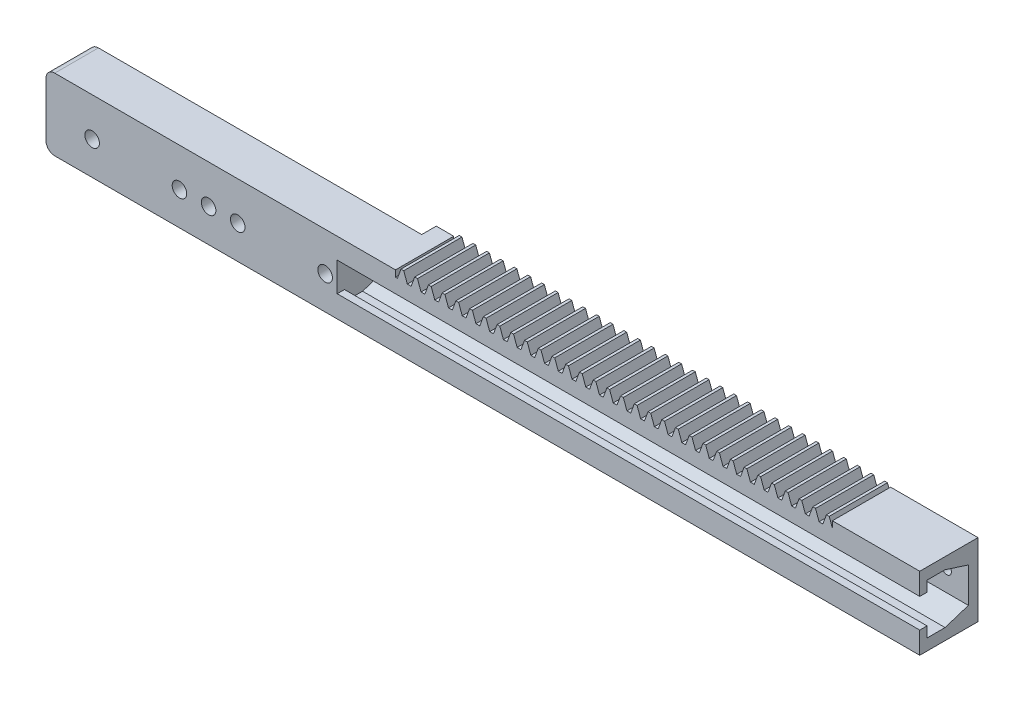
SolidWorks part; units mm, degrees
extrude "Blank" add sketch "BlankSke" against normal blind 20
sketch "BlankSke" plane through (0, 0, 0) normal (0, 0, 1) x (1, 0, 0)
  line L1 (0, 0) -> (150, 0)
  line L2 (0, 0) -> (0, 11.5)
  line L3 (0, 11.5) -> (150, 11.5)
  line L4 (150, 0) -> (150, 11.5)
  dimension "Length" = 150
  dimension "Blank_height" = 11.5
ref_plane "Plane1" through (0, 0, 0) normal (0, 0, 1) x (1, 0, 0)
ref_plane "Plane2" through (0, 0, 0) normal (0, 1, 0) x (1, 0, 0)
ref_plane "Plane3" through (0, 0, 0) normal (1, 0, 0) x (0, 0, -1)
other "Configuration Table"
sketch "HoldingSke" plane through (0, 0, 0) normal (0, 1, 0) x (1, 0, 0)
  line L0 (0, 0) -> (0.0928, 0.6602)
  line L1 (-15, 0) -> (100, 0) construction
  line L2 (0, 0) -> (-2.1039, 2.3779)
  line L3 (0, 0) -> (-11.863, 4.5341)
  line L4 (0, 0) -> (7.2428, 4.7035)
  line L5 (0, 0) -> (-23.7986, -8.8762)
  line L6 (0, 0) -> (-10.5278, -7.1032)
  line L9 (-71.009, 38.7566) -> (69.9449, 90.0596)
  line L10 (-76.2, 3.8779) -> (-66.2, 3.8779)
  line L11 (0, 0) -> (-20, 0)
  line L12 (-76.2, 101.6) -> (-76.147, 101.6)
  line L13 (24.9733, 27.94) -> (52.9518, 28.4284)
  line L14 (24.9733, 27.94) -> (24.9743, 27.94)
  line L15 (24.9733, 27.94) -> (100.4006, 29.5858)
  circle A0 centre (0, 0) radius 19.05
  circle A1 centre (0, 0) radius 5
  circle A2 centre (0, 0) radius 12.7
  dimension "MPH" = 10
  dimension "Diameter" = 38.1
  dimension "Num_teeth" = 33
  dimension "Pitch" = 0.6667
  dimension "Show_teeth" = 998
  dimension "Thickness" = 12.7
  dimension "Ap" = 20
  dimension "Pitch_height" = 10
  dimension "Width" = 20
  dimension "Backlash" = 0.053
  dimension "Addendum_fac" = 1
  dimension "Dedendum_fac" = 1.25
  dimension "Clearance_fac" = 0.25
  dimension "Dedendum_add" = 0.001
  dimension "Length" = 150
  dimension "Module" = 1.5
sketch "TooCutSkeIll" plane through (0, 0, 0) normal (0, 0, 1) x (1, 0, 0)
  line L0 (-1.8687, 11.4605) -> (-0.7447, 8.3724)
  line L1 (-0.3914, 8.125) -> (0.3914, 8.125)
  line L2 (0.7447, 8.3724) -> (1.8687, 11.4605)
  line L3 (150, 11.5) -> (0, 11.5) construction
  line L4 (0, 0) -> (0, 64.897) construction
  line L5 (-13.208, 10) -> (12.954, 10) construction
  line L6 (0, 0) -> (150, 0) construction
  line L7 (1.3371, 10) -> (1.3371, 48.7463) construction
  line L8 (-1.3371, 10) -> (-1.3371, 48.7463) construction
  line L9 (1.9251, 11.5) -> (1.9251, 11.5254)
  line L10 (-1.9251, 11.5) -> (-1.9251, 11.5254)
  line L11 (-1.9251, 11.5254) -> (1.9251, 11.5254)
  arc A0 (0.3914, 8.125) -> (0.7447, 8.3724) centre (0.3914, 8.501) ccw
  arc A1 (-0.7447, 8.3724) -> (-0.3914, 8.125) centre (-0.3914, 8.501) ccw
  arc A2 (1.9251, 11.5) -> (1.8687, 11.4605) centre (1.9251, 11.44) ccw
  arc A3 (-1.8687, 11.4605) -> (-1.9251, 11.5) centre (-1.9251, 11.44) ccw
  dimension "Pitch_height" = 10
  dimension "Addendum_plus" = 1.5254
  dimension "Pressure_angle" = 20
  dimension "Gap_width" = 2.6742
  dimension "Dedendum" = 1.875
extrude "ToothCutIll" [suppressed] cut sketch "TooCutSkeIll" against normal through all
sketch "TooCutSkeSim" plane through (0, 0, 0) normal (0, 0, 1) x (1, 0, 0)
  line L0 (0.6547, 8.125) -> (-0.6547, 8.125)
  line L1 (1.8923, 11.5254) -> (0.6547, 8.125)
  line L2 (0, 17.4625) -> (0, 53.467) construction
  line L3 (1.8923, 11.5254) -> (-1.8923, 11.5254)
  line L6 (-1.8923, 11.5254) -> (-0.6547, 8.125)
  line L9 (-1.3371, 10) -> (1.3371, 10) construction
  line L10 (0, 0) -> (150, 0) construction
  line L11 (1.3371, 10) -> (1.3371, 53.467) construction
  line L12 (-1.3371, 10) -> (-1.3371, 53.467) construction
  dimension "Pitch_height" = 10
  dimension "Addendum_plus" = 1.5254
  dimension "Pressure_angle" = 20
  dimension "Gap_width" = 2.6742
  dimension "Dedendum" = 1.875
extrude "ToothCutSim" cut sketch "TooCutSkeSim" against normal through all
pattern_linear "TeethCuts" count 32 spacing 4.7124 along (1, 0, 0) of "ToothCutIll", "ToothCutSim"
sketch "Sketch1" plane through (150, 0, 0) normal (1, 0, 0) x (0, 0, -1)
  line L0 (0, 8.5146) -> (0, 10.7146)
  line L1 (0, 8.5146) -> (0, 11.5) construction
  line L2 (0, 10.7146) -> (20, 10.7146)
  line L3 (20, 11.5) -> (20, 8.5146) construction
  line L7 (0, 8.5146) -> (0, 0)
  line L8 (0, 0) -> (20, 0)
  line L9 (20, 0) -> (20, 10.7146)
extrude "Boss-Extrude1" add sketch "Sketch1" along normal blind 20
sketch "Sketch2" plane through (0, 0, 0) normal (-1, 0, 0) x (0, 0, 1)
  line L0 (-20, 8.125) -> (-20, 10.325)
  line L1 (-20, 8.125) -> (-20, 11.5) construction
  line L2 (-20, 10.325) -> (0, 10.325)
  line L3 (0, 8.125) -> (0, 11.5) construction
  line L4 (0, 10.325) -> (0, 0)
  line L5 (0, 0) -> (-20, 0)
  line L6 (-20, 0) -> (-20, 8.125)
extrude "Boss-Extrude2" add sketch "Sketch2" along normal blind 20
sketch "Sketch3" plane through (0, 0, 0) normal (0, -1, 0) x (1, 0, 0)
  line L1 (-20, 0) -> (170, 0)
  line L2 (-20, 0) -> (-20, -20)
  line L3 (-20, -20) -> (170, -20)
  line L4 (170, 0) -> (170, -20)
extrude "Boss-Extrude3" add sketch "Sketch3" along normal blind 14.285
sketch "Sketch4" plane through (170, 0, 0) normal (1, 0, 0) x (0, 0, -1)
  line L2 (0, 10.7146) -> (0, -14.285) construction
  line L4 (2.5, -10.3852) -> (2.5, -6.7852)
  line L5 (2.5, 6.8148) -> (8.7, 6.8148)
  line L7 (16.7, 4.2148) -> (16.7, -7.7852)
  line L8 (16.7, -7.7852) -> (8.7, -10.3852)
  line L9 (16.7, -1.7852) -> (16.7, 4.2148)
  line L10 (16.7, 4.2148) -> (8.7, 6.8148)
  line L11 (2.5, -10.3852) -> (8.7, -10.3852)
  line L12 (0, -1.7852) -> (0, 3.2148)
  line L13 (0, 3.2148) -> (2.5, 3.2148)
  line L15 (2.5, -6.7852) -> (0, -6.7852)
  line L16 (0, -6.7852) -> (0, 3.2148)
  line L17 (2.5, 3.2148) -> (2.5, 6.8148)
  line M11 (0, 10.7146) -> (0, -14.285)
extrude "Cut-Extrude1" cut sketch "Sketch4" against normal through all contours L17 L13 L15 L4 L11 L8 L7 L10 L5 M11
sketch "Sketch6" plane through (-20, 0, 0) normal (-1, 0, 0) x (0, 0, 1)
  line L1 (-20, -14.285) -> (0, -14.285)
  line L2 (-20, -14.285) -> (-20, 10.325)
  line L3 (-20, 10.325) -> (0, 10.325)
  line L4 (0, -14.285) -> (0, 10.325)
extrude "Boss-Extrude4" add sketch "Sketch6" along normal blind 140
sketch "Sketch8" plane through (170, 0, 0) normal (1, 0, 0) x (0, 0, -1)
  line L0 (20, 10.7146) -> (20, -14.285)
  line L1 (20, -14.285) -> (0, -14.285)
  line L2 (0, -14.285) -> (0, -6.7852)
  line L3 (0, -6.7852) -> (2.5, -6.7852)
  line L4 (2.5, -6.7852) -> (2.5, -10.3852)
  line L5 (2.5, -10.3852) -> (8.7, -10.3852) construction
  line L6 (2.5, -10.3852) -> (2.5, -6.7852) construction
  line L7 (2.5, -10.3852) -> (8.7, -10.3852)
  line L8 (8.7, -10.3852) -> (16.7, -7.7852)
  line L9 (16.7, -7.7852) -> (16.7, 4.2148)
  line L10 (16.7, 4.2148) -> (8.7, 6.8148)
  line L11 (8.7, 6.8148) -> (2.5, 6.8148)
  line L12 (2.5, 6.8148) -> (2.5, 3.2148)
  line L13 (2.5, 3.2148) -> (0, 3.2148)
  line L14 (0, 3.2148) -> (0, 10.7146)
  line L15 (0, 10.7146) -> (20, 10.7146)
extrude "Boss-Extrude5" add sketch "Sketch8" along normal blind 10
sketch "Sketch9" plane through (0, 0, -20) normal (0, 0, -1) x (-1, 0, 0)
  circle A0 centre (24.1693, -2.8898) radius 2.5
  circle A1 centre (54.1693, -2.8898) radius 2.5
  circle A2 centre (64.1693, -2.8898) radius 2.5
  circle A3 centre (74.1693, -2.8898) radius 2.5
  circle A4 centre (104.1693, -2.8898) radius 2.5
extrude "Cut-Extrude2" cut sketch "Sketch9" against normal through all
sketch "Sketch10" plane through (-160, 0, 0) normal (-1, 0, 0) x (0, 0, 1)
  line L0 (-20, -14.285) -> (-15, -14.285)
  line L1 (-20, -14.285) -> (0, -14.285) construction
  line L2 (-15, -14.285) -> (-15, 10.325)
  line L3 (0, 10.325) -> (-20, 10.325) construction
  line L5 (-20, 10.325) -> (-20, -14.285)
  line L6 (-20, 10.325) -> (-20, 11.5)
  line L7 (-20, 11.5) -> (-15, 11.5)
  line L8 (0, 11.5) -> (-20, 11.5) construction
  line L9 (-15, 11.5) -> (-15, 10.325)
extrude "Cut-Extrude5" cut sketch "Sketch10" against normal blind 154 and the other way through all
sketch "Sketch15" plane through (0, -14.285, 0) normal (0, -1, 0) x (1, 0, 0)
  line L0 (-9.9264, -15) -> (-9.9264, 0)
  line L1 (-160, -15) -> (-6, -15) construction
  line L2 (180, 0) -> (-160, 0) construction
  line L3 (-9.9264, -15) -> (-12.4264, -15)
  line L4 (-12.4264, -15) -> (-12.4264, 0)
  line L5 (-12.4264, 0) -> (-9.9264, 0)
extrude "Boss-Extrude9" add sketch "Sketch15" along normal blind 10
sketch "Sketch16" plane through (-12.4264, 0, 0) normal (-1, 0, 0) x (0, 0, 1)
  circle A0 centre (-11.25, -19.285) radius 2
  circle A1 centre (-3.75, -19.285) radius 2
extrude "Cut-Extrude7" cut sketch "Sketch16" against normal blind 10
sketch "Sketch17" plane through (-160, 0, 0) normal (-1, 0, 0) x (0, 0, 1)
  line L1 (-15, -14.285) -> (0, -14.285)
  line L2 (-15, -14.285) -> (-15, -24.285)
  line L3 (-15, -24.285) -> (0, -24.285)
  line L4 (0, -14.285) -> (0, -24.285)
extrude "Cut-Extrude8" cut sketch "Sketch17" against normal blind 177
sketch "Sketch19" plane through (0, 10.325, 0) normal (0, 1, 0) x (1, 0, 0)
  line L7 (-160, 7.5) -> (-132.3342, 7.5)
  line L8 (-160, 0) -> (-160, 15) construction
sketch "Sketch20" plane through (-160, 0, 0) normal (-1, 0, 0) x (0, 0, 1)
  line L1 (0, -14.285) -> (-15, -14.285)
  line L2 (0, -14.285) -> (0, 10.325)
  line L3 (0, 10.325) -> (-15, 10.325)
  line L4 (-15, -14.285) -> (-15, 10.325)
extrude "Cut-Extrude9" cut sketch "Sketch20" against normal blind 40
fillet "Fillet2" radius 3 2 edges at (-120, 10.325, -7.5) (-120, -14.285, -7.5)
sketch "Sketch21" plane through (0, 0, -20) normal (0, 0, -1) x (-1, 0, 0)
  circle A0 centre (-172.561, -0.7852) radius 1.6
  circle A1 centre (-162.561, -0.7852) radius 1.6
extrude "Cut-Extrude10" cut sketch "Sketch21" against normal blind 40
equation "' \"Module@HoldingSke\" = 6.35"
equation "' \"Num_teeth@HoldingSke\" = 12"
equation "' \"Ap@HoldingSke\" =  20"
equation "' \"Ap@HoldingSke\" = 20"
equation "' \"Width@HoldingSke\" = 0.25 * 25.4"
equation "' \"Show_teeth@HoldingSke\" = 500"
equation "' \"Backlash@HoldingSke\" = 0.009 * 25.4"
equation "' \"Addendum_fac@HoldingSke\" = 1.0"
equation "' \"Dedendum_fac@HoldingSke\" = 1.25"
equation "' \"Dedendum_add@HoldingSke\" = 0.00005 * 25.4"
equation "' \"Clearance_fac@HoldingSke\" = 0.25"
equation "' \"Pitch_height@HoldingSke\" = 1 * 25.4"
equation "' \"Length@HoldingSke\" = 4.71 * 25.4"
equation "\"Pitch@HoldingSke\" = 1 / \"Module@HoldingSke\""
equation "\"MPH@HoldingSke\" = \"Dedendum_fac@HoldingSke\" / \"Pitch@HoldingSke\" + 2 * \"Dedendum_add@HoldingSke\" + 0.002 * 25.4"
equation "\"MPH@HoldingSke\" = ((sgn( \"MPH@HoldingSke\" - \"Pitch_height@HoldingSke\")+1)*( \"MPH@HoldingSke\" - \"Pitch_height@HoldingSke\"))/2 + \"Pitch_height@HoldingSke\""
equation "\"Blank_height@BlankSke\" = \"Pitch_height@HoldingSke\" + \"Addendum_fac@HoldingSke\"  / \"Pitch@HoldingSke\" "
equation "\"Length@BlankSke\" =  \"Length@HoldingSke\""
equation "\"Face_width@Blank\" = \"Width@HoldingSke\""
equation "\"Pressure_angle@TooCutSkeIll\" = \"Ap@HoldingSke\""
equation "\"Addendum_plus@TooCutSkeIll\" =  \"Addendum_fac@HoldingSke\"  / \"Pitch@HoldingSke\" + 0.001 *25.4"
equation "\"Dedendum@TooCutSkeIll\" = \"Dedendum_fac@HoldingSke\"  / \"Pitch@HoldingSke\""
equation "\"Pitch_height@TooCutSkeIll\" =  \"MPH@HoldingSke\""
equation "\"Gap_width@TooCutSkeIll\" = 3.14159265 / 2 / \"Pitch@HoldingSke\" + 6 * \"Backlash@HoldingSke\""
equation "\"Pressure_angle@TooCutSkeSim\" = \"Ap@HoldingSke\""
equation "\"Addendum_plus@TooCutSkeSim\" =  \"Addendum_fac@HoldingSke\"  / \"Pitch@HoldingSke\" + 0.001 * 25.4"
equation "\"Dedendum@TooCutSkeSim\" = \"Dedendum_fac@HoldingSke\"  / \"Pitch@HoldingSke\""
equation "\"Pitch_height@TooCutSkeSim\" =  \"MPH@HoldingSke\""
equation "\"Gap_width@TooCutSkeSim\" = 3.14159265 / 2 / \"Pitch@HoldingSke\" + 6 * \"Backlash@HoldingSke\""
equation "\"Root_fillet@TooCutSkeIll\" = \"Clearance_fac@HoldingSke\" / \"Pitch@HoldingSke\" + \"Dedendum_add@HoldingSke\""
equation "\"Break_rad@TooCutSkeIll\" = 0.02 / \"Pitch@HoldingSke\" * 2"
equation "\"Linear_pitch@TeethCuts\" = 3.14159265 / \"Pitch@HoldingSke\""
equation "\"Num_teeth@HoldingSke\" = int( ( \"Length@HoldingSke\" + 0 ) / (3.14159265 / \"Pitch@HoldingSke\")) + 0.9999  + 1"
equation " \"Num_teeth@TeethCuts\" = int( \"Show_teeth@HoldingSke\" ) + 1"
equation " \"Num_teeth@TeethCuts\" = ((sgn( \"Num_teeth@TeethCuts\" - \"Num_teeth@HoldingSke\" )-1)*( \"Num_teeth@TeethCuts\" - \"Num_teeth@HoldingSke\" ))/-2+ \"Num_teeth@HoldingSke\""
equation " \"Num_teeth@TeethCuts\" = ((sgn( \"Num_teeth@TeethCuts\" - 2.0)+1)*( \"Num_teeth@TeethCuts\" - 2.0))/2 +2.0"
